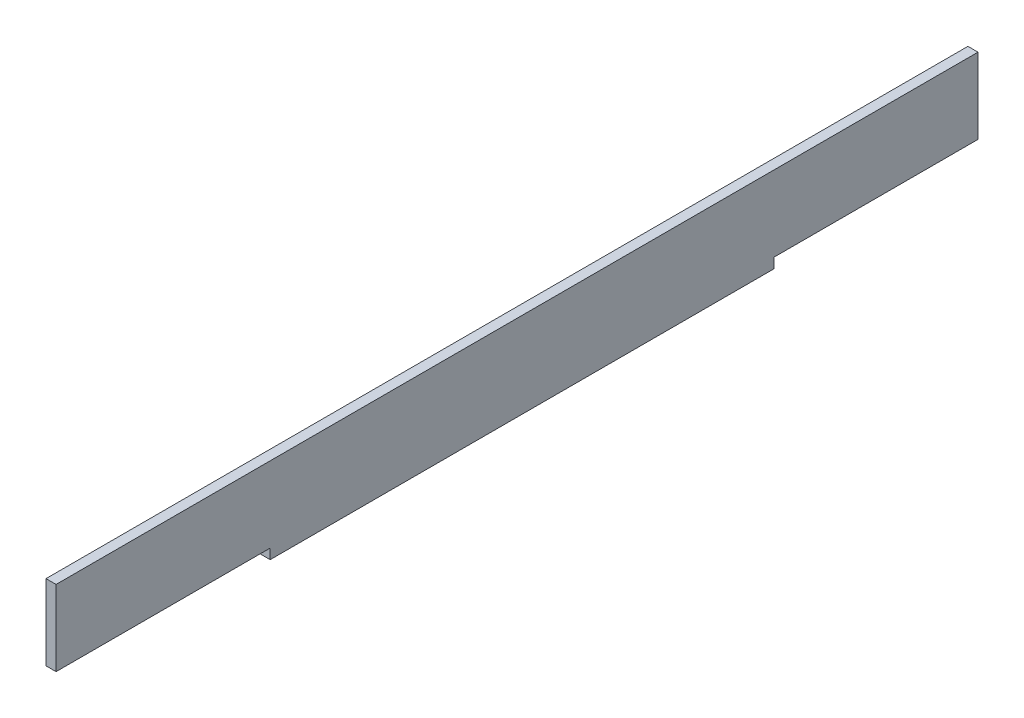
SolidWorks part; units mm, degrees
ref_plane "Front Plane" through (0, 0, 0) normal (0, 0, 1) x (1, 0, 0)
ref_plane "Top Plane" through (0, 0, 0) normal (0, 1, 0) x (1, 0, 0)
ref_plane "Right Plane" through (0, 0, 0) normal (1, 0, 0) x (0, 0, -1)
sketch "Sketch1" plane through (0, 0, 0) normal (1, 0, 0) x (0, 0, -1)
  line L0 (-103.8087, -19.0875) -> (96.1913, -19.0875)
  line L1 (96.1913, -19.0875) -> (96.1913, -15.0875)
  line L2 (96.1913, -15.0875) -> (177.1913, -15.0875)
  line L3 (177.1913, -15.0875) -> (177.1913, 14.9125)
  line L4 (177.1913, 14.9125) -> (96.1913, 14.9125)
  line L5 (96.1913, 14.9125) -> (-103.8087, 14.9125)
  line L6 (-103.8087, 14.9125) -> (-188.8087, 14.9125)
  line L7 (-188.8087, 14.9125) -> (-188.8087, -15.0875)
  line L8 (-188.8087, -15.0875) -> (-103.8087, -15.0875)
  line L9 (-103.8087, -15.0875) -> (-103.8087, -19.0875)
  dimension "D1" = 200
  dimension "D2" = 4
  dimension "D3" = 81
  dimension "D4" = 30
  dimension "D5" = 200
  dimension "D6" = 85
  dimension "D7" = 30
  dimension "D8" = 85
  dimension "D9" = 4
extrude "Boss-Extrude1" add sketch "Sketch1" along normal blind 4
